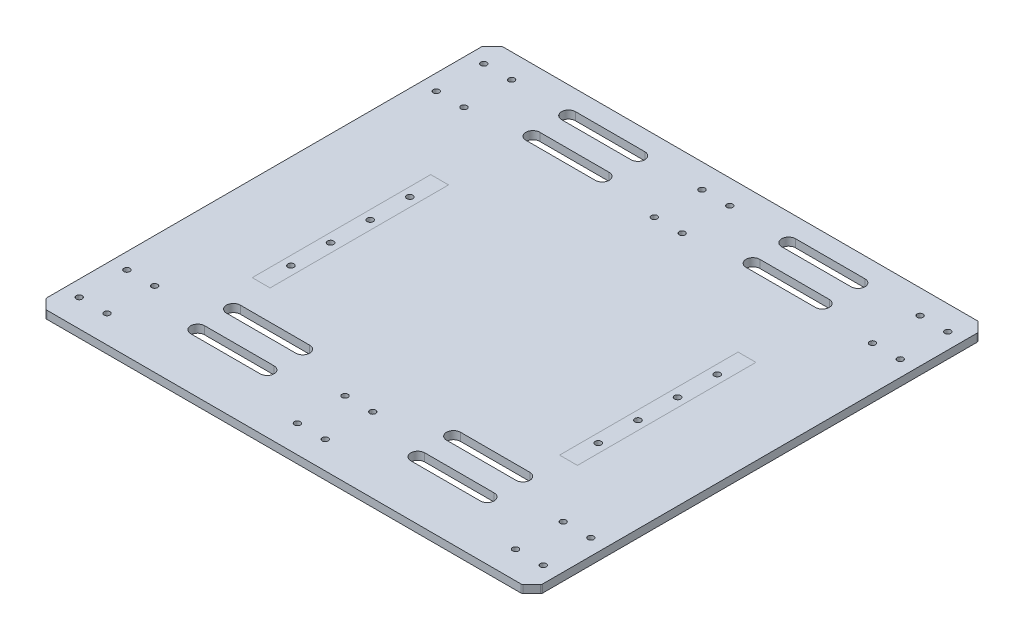
SolidWorks part; units mm, degrees
material "Thornel Mat VMA"
ref_plane "前视基准面" through (0, 0, 0) normal (0, 0, 1) x (1, 0, 0)
ref_plane "上视基准面" through (0, 0, 0) normal (0, 1, 0) x (1, 0, 0)
ref_plane "右视基准面" through (0, 0, 0) normal (1, 0, 0) x (0, 0, -1)
sketch "草图1" plane through (0, 0, 0) normal (0, 1, 0) x (1, 0, 0)
  line L1 (-125, 115) -> (125, 115)
  line L2 (-125, 115) -> (-125, -115)
  line L3 (-125, -115) -> (125, -115)
  line L4 (125, 115) -> (125, -115)
  line L5 (0, -115) -> (0, 115) construction
  line L6 (-125, 0) -> (125, 0) construction
  point P44 (0, 0)
  dimension "D1" = 250
  dimension "D2" = 230
extrude "凸台-拉伸1" add sketch "草图1" along normal blind 4
sketch "草图2" plane through (0, 4, 0) normal (0, 1, 0) x (1, 0, 0)
  line L0 (0, 172.9489) -> (0, 0) construction
  line L1 (0, 0) -> (-225.9448, 0) construction
  line L2 (125, 115) -> (-125, 115) construction
  line L3 (-125, 115) -> (-125, -115) construction
  line L4 (-11, 0) -> (-11, 120.2888) construction
  line L5 (-115, 85) -> (115, 85) construction
  circle A0 centre (-115, 107.5) radius 2.05
  circle A1 centre (-115, 85) radius 2.05
  circle A2 centre (-115, 62.5) radius 2.05
  circle A3 centre (-115, -62.5) radius 2.05
  circle A4 centre (-115, -85) radius 2.05
  circle A5 centre (-115, -107.5) radius 2.05
  circle A6 centre (115, -107.5) radius 2.05
  circle A7 centre (115, -85) radius 2.05
  circle A8 centre (115, -62.5) radius 2.05
  circle A9 centre (115, 62.5) radius 2.05
  circle A10 centre (115, 85) radius 2.05
  circle A11 centre (115, 107.5) radius 2.05
  circle A12 centre (-115, 27.5) radius 2.05
  circle A13 centre (-115, -27.5) radius 2.05
  circle A14 centre (115, -27.5) radius 2.05
  circle A15 centre (115, 27.5) radius 2.05
  circle A16 centre (-11, 27.5) radius 2.05
  circle A17 centre (11, 27.5) radius 2.05
  circle A18 centre (11, -27.5) radius 2.05
  circle A19 centre (-11, -27.5) radius 2.05
  circle A20 centre (-11, 105) radius 2.05
  circle A21 centre (-11, 65) radius 2.05
  circle A22 centre (11, 65) radius 2.05
  circle A23 centre (11, 105) radius 2.05
  circle A24 centre (11, -105) radius 2.05
  circle A25 centre (11, -65) radius 2.05
  circle A26 centre (-11, -65) radius 2.05
  circle A27 centre (-11, -105) radius 2.05
  dimension "D1" = 7.5
  dimension "D2" = 22.5
  dimension "D3" = 22.5
  dimension "D4" = 4.1
  dimension "D5" = 10
  dimension "D6" = 4.1
  dimension "D7" = 27.5
  dimension "D9" = 55
  dimension "D10" = 40
  dimension "D11" = 4.1
  dimension "D8" = 11
extrude "切除-拉伸1" [suppressed] cut sketch "草图2" against normal blind 3
sketch "草图3" [suppressed] plane through (0, 3, 0) normal (0, 1, 0) x (1, 0, 0)
  line L0 (-145, 77.5) -> (145, 77.5) construction
  line L1 (0, 0) -> (0, 207.4838) construction
  line L2 (0, 0) -> (-163.0606, 0) construction
  circle A0 centre (-120, 92.5) radius 2.05
  circle A1 centre (-145, 100) radius 2.05 construction
  circle A2 centre (-120, 62.5) radius 2.05
  circle A3 centre (120, 62.5) radius 2.05
  circle A4 centre (120, 92.5) radius 2.05
  circle A5 centre (120, -92.5) radius 2.05
  circle A6 centre (120, -62.5) radius 2.05
  circle A7 centre (-120, -62.5) radius 2.05
  circle A8 centre (-120, -92.5) radius 2.05
  circle A9 centre (-30, 92.5) radius 2.05
  circle A10 centre (-30, 62.5) radius 2.05
  circle A11 centre (30, 62.5) radius 2.05
  circle A12 centre (30, 92.5) radius 2.05
  circle A13 centre (30, -92.5) radius 2.05
  circle A14 centre (30, -62.5) radius 2.05
  circle A15 centre (-30, -62.5) radius 2.05
  circle A16 centre (-30, -92.5) radius 2.05
  dimension "D1" = 4.1
  dimension "D2" = 30
  dimension "D3" = 25
  dimension "D4" = 4.1
  dimension "D5" = 90
  dimension "D6" = 30
extrude "切除-拉伸2" [suppressed] cut sketch "草图3" against normal blind 3
sketch "草图4" plane through (0, 4, 0) normal (0, 1, 0) x (1, 0, 0)
  circle B0 centre (50, -77.5) radius 15.25 construction
  circle B1 centre (58.8388, -68.6612) radius 1.5 construction
  circle B2 centre (58.8388, -86.3388) radius 1.5 construction
  circle B3 centre (41.1612, -86.3388) radius 1.5 construction
  circle B4 centre (41.1612, -68.6612) radius 1.5 construction
  circle B5 centre (50, -77.5) radius 6 construction
  circle B6 centre (60, 77.5) radius 15.25 construction
  circle B7 centre (68.8388, 68.6612) radius 1.5 construction
  circle B8 centre (68.8388, 86.3388) radius 1.5 construction
  circle B9 centre (51.1612, 86.3388) radius 1.5 construction
  circle B10 centre (51.1612, 68.6612) radius 1.5 construction
  circle B11 centre (60, 77.5) radius 6 construction
  circle B12 centre (-50, 77.5) radius 15.25 construction
  circle B13 centre (-58.8388, 68.6612) radius 1.5 construction
  circle B14 centre (-58.8388, 86.3388) radius 1.5 construction
  circle B15 centre (-41.1612, 86.3388) radius 1.5 construction
  circle B16 centre (-41.1612, 68.6612) radius 1.5 construction
  circle B17 centre (-50, 77.5) radius 6 construction
  circle B18 centre (-50, -77.5) radius 15.25 construction
  circle B19 centre (-58.8388, -68.6612) radius 1.5 construction
  circle B20 centre (-58.8388, -86.3388) radius 1.5 construction
  circle B21 centre (-41.1612, -86.3388) radius 1.5 construction
  circle B22 centre (-41.1612, -68.6612) radius 1.5 construction
  circle B23 centre (-50, -77.5) radius 6 construction
  circle B24 centre (60, -77.5) radius 15.25 construction
  circle B25 centre (68.8388, -68.6612) radius 1.5 construction
  circle B26 centre (68.8388, -86.3388) radius 1.5 construction
  circle B27 centre (51.1612, -86.3388) radius 1.5 construction
  circle B28 centre (51.1612, -68.6612) radius 1.5 construction
  circle B29 centre (60, -77.5) radius 6 construction
  circle B30 centre (-60, -77.5) radius 15.25 construction
  circle B31 centre (-68.8388, -68.6612) radius 1.5 construction
  circle B32 centre (-68.8388, -86.3388) radius 1.5 construction
  circle B33 centre (-51.1612, -86.3388) radius 1.5 construction
  circle B34 centre (-51.1612, -68.6612) radius 1.5 construction
  circle B35 centre (-60, -77.5) radius 6 construction
  circle B36 centre (-60, 77.5) radius 15.25 construction
  circle B37 centre (-68.8388, 68.6612) radius 1.5 construction
  circle B38 centre (-68.8388, 86.3388) radius 1.5 construction
  circle B39 centre (-51.1612, 86.3388) radius 1.5 construction
  circle B40 centre (-51.1612, 68.6612) radius 1.5 construction
  circle B41 centre (-60, 77.5) radius 6 construction
  circle B42 centre (50, 77.5) radius 15.25 construction
  circle B43 centre (58.8388, 68.6612) radius 1.5 construction
  circle B44 centre (58.8388, 86.3388) radius 1.5 construction
  circle B45 centre (41.1612, 86.3388) radius 1.5 construction
  circle B46 centre (41.1612, 68.6612) radius 1.5 construction
  circle B47 centre (50, 77.5) radius 6 construction
  line B48 (50, -77.5) -> (41.1612, -68.6612) construction
  line B49 (0, -217.5) -> (0, 150.3134) construction
  line B50 (60, -77.5) -> (51.1612, -68.6612) construction
  line B51 (145, 77.5) -> (145, -77.5) construction
  line B52 (145, 0) -> (-145, 0) construction
  line B53 (60, 77.5) -> (51.1612, 68.6612) construction
  line B54 (50, 77.5) -> (41.1612, 68.6612) construction
  line B55 (-55, 77.5) -> (3.1224, 77.5) construction
  line B56 (50, -77.5) -> (60, -77.5) construction
  line B57 (50, -61.5) -> (60, -61.5) construction
  line B58 (50, -93.5) -> (60, -93.5) construction
  line B59 (-50, -77.5) -> (-60, -77.5) construction
  line B60 (-50, -61.5) -> (-60, -61.5) construction
  line B61 (-50, -93.5) -> (-60, -93.5) construction
  line B62 (-50, 77.5) -> (-60, 77.5) construction
  line B63 (-50, 61.5) -> (-60, 61.5) construction
  line B64 (-50, 93.5) -> (-60, 93.5) construction
  line B65 (50, 77.5) -> (60, 77.5) construction
  line B66 (50, 61.5) -> (60, 61.5) construction
  line B67 (50, 93.5) -> (60, 93.5) construction
  line B68 (-68.8388, 86.3388) -> (-41.1612, 86.3388) construction
  line B69 (-68.8388, 89.8388) -> (-41.1612, 89.8388)
  line B70 (-68.8388, 82.8388) -> (-41.1612, 82.8388)
  line B71 (68.8388, 86.3388) -> (41.1612, 86.3388) construction
  line B72 (68.8388, 89.8388) -> (41.1612, 89.8388)
  line B73 (68.8388, 82.8388) -> (41.1612, 82.8388)
  line B74 (68.8388, 68.6612) -> (41.1612, 68.6612) construction
  line B75 (68.8388, 65.1612) -> (41.1612, 65.1612)
  line B76 (68.8388, 72.1612) -> (41.1612, 72.1612)
  line B77 (-68.8388, 68.6612) -> (-41.1612, 68.6612) construction
  line B78 (-68.8388, 65.1612) -> (-41.1612, 65.1612)
  line B79 (-68.8388, 72.1612) -> (-41.1612, 72.1612)
  line B80 (-68.8388, -86.3388) -> (-41.1612, -86.3388) construction
  line B81 (-68.8388, -89.8388) -> (-41.1612, -89.8388)
  line B82 (-68.8388, -82.8388) -> (-41.1612, -82.8388)
  line B83 (-68.8388, -68.6612) -> (-41.1612, -68.6612) construction
  line B84 (-68.8388, -65.1612) -> (-41.1612, -65.1612)
  line B85 (-68.8388, -72.1612) -> (-41.1612, -72.1612)
  line B86 (68.8388, -86.3388) -> (41.1612, -86.3388) construction
  line B87 (68.8388, -89.8388) -> (41.1612, -89.8388)
  line B88 (68.8388, -82.8388) -> (41.1612, -82.8388)
  line B89 (68.8388, -68.6612) -> (41.1612, -68.6612) construction
  line B90 (68.8388, -65.1612) -> (41.1612, -65.1612)
  line B91 (68.8388, -72.1612) -> (41.1612, -72.1612)
  arc B92 (50, -61.5) -> (50, -93.5) centre (50, -77.5) ccw construction
  arc B93 (60, -93.5) -> (60, -61.5) centre (60, -77.5) ccw construction
  arc B94 (-50, -61.5) -> (-50, -93.5) centre (-50, -77.5) cw construction
  arc B95 (-60, -93.5) -> (-60, -61.5) centre (-60, -77.5) cw construction
  arc B96 (-50, 61.5) -> (-50, 93.5) centre (-50, 77.5) ccw construction
  arc B97 (-60, 93.5) -> (-60, 61.5) centre (-60, 77.5) ccw construction
  arc B98 (50, 61.5) -> (50, 93.5) centre (50, 77.5) cw construction
  arc B99 (60, 93.5) -> (60, 61.5) centre (60, 77.5) cw construction
  arc B100 (-68.8388, 89.8388) -> (-68.8388, 82.8388) centre (-68.8388, 86.3388) ccw
  arc B101 (-41.1612, 82.8388) -> (-41.1612, 89.8388) centre (-41.1612, 86.3388) ccw
  arc B102 (68.8388, 89.8388) -> (68.8388, 82.8388) centre (68.8388, 86.3388) cw
  arc B103 (41.1612, 82.8388) -> (41.1612, 89.8388) centre (41.1612, 86.3388) cw
  arc B104 (68.8388, 65.1612) -> (68.8388, 72.1612) centre (68.8388, 68.6612) ccw
  arc B105 (41.1612, 72.1612) -> (41.1612, 65.1612) centre (41.1612, 68.6612) ccw
  arc B106 (-68.8388, 65.1612) -> (-68.8388, 72.1612) centre (-68.8388, 68.6612) cw
  arc B107 (-41.1612, 72.1612) -> (-41.1612, 65.1612) centre (-41.1612, 68.6612) cw
  arc B108 (-68.8388, -89.8388) -> (-68.8388, -82.8388) centre (-68.8388, -86.3388) cw
  arc B109 (-41.1612, -82.8388) -> (-41.1612, -89.8388) centre (-41.1612, -86.3388) cw
  arc B110 (-68.8388, -65.1612) -> (-68.8388, -72.1612) centre (-68.8388, -68.6612) ccw
  arc B111 (-41.1612, -72.1612) -> (-41.1612, -65.1612) centre (-41.1612, -68.6612) ccw
  arc B112 (68.8388, -89.8388) -> (68.8388, -82.8388) centre (68.8388, -86.3388) ccw
  arc B113 (41.1612, -82.8388) -> (41.1612, -89.8388) centre (41.1612, -86.3388) ccw
  arc B114 (68.8388, -65.1612) -> (68.8388, -72.1612) centre (68.8388, -68.6612) cw
  arc B115 (41.1612, -72.1612) -> (41.1612, -65.1612) centre (41.1612, -68.6612) cw
sketch_block_instance "槽口-1"
sketch_block "槽口" parameters "D3"=16, "D4"=3.5, "D5"=3.5, "D1"=100, "D2"=120
sketch_block_instance "3510电机安装孔位-1"
sketch_block "3510电机安装孔位"
sketch_block_instance "3510电机安装孔位-1"
sketch_block_instance "3510电机安装孔位-2"
sketch_block_instance "3510电机安装孔位-3"
sketch_block_instance "3510电机安装孔位-4"
sketch_block_instance "3510电机安装孔位-5"
sketch_block_instance "3510电机安装孔位-6"
sketch_block_instance "3510电机安装孔位-7"
extrude "切除-拉伸3" [suppressed] cut sketch "草图4" against normal blind 3 contours B70 B101 B69 B100 | B107 B79 B106 B78 | B103 B73 B102 B72 | B76 B105 B75 B104 | B115 B91 B114 B90 | B88 B113 B87 B112 | B85 B111 B84 B110 | B109 B82 B108 B81
sketch "草图5" plane through (0, 4, 0) normal (0, 1, 0) x (1, 0, 0)
  line L0 (0, 125.0534) -> (0, -12) construction
  line L1 (0, -12) -> (98.1075, -12) construction
  line L2 (77.5, 34.0359) -> (77.5, -32.2485) construction
  circle A0 centre (77.5, -2) radius 1.55
  circle A1 centre (77.5, 18) radius 1.55
  circle A2 centre (77.5, -22) radius 1.55
  circle A3 centre (77.5, -42) radius 1.55
  circle A4 centre (-77.5, -42) radius 1.55
  circle A5 centre (-77.5, -22) radius 1.55
  circle A6 centre (-77.5, 18) radius 1.55
  circle A7 centre (-77.5, -2) radius 1.55
  dimension "D2" = 3.1
  dimension "D3" = 20
  dimension "D4" = 20
  dimension "D1" = 77.5
  dimension "D5" = 12
extrude "切除-拉伸4" cut sketch "草图5" against normal blind 3
sketch "草图6" plane through (0, 4, 0) normal (0, 1, 0) x (1, 0, 0)
  line L0 (-77.5, 18) -> (-77.5, -42) construction
  line L1 (-73, 33) -> (-82, 33)
  line L2 (-73, 33) -> (-73, -57)
  line L3 (-73, -57) -> (-82, -57)
  line L4 (-82, 33) -> (-82, -57)
  line L5 (-77.5, -57) -> (-77.5, 33) construction
  line L6 (-73, -12) -> (-82, -12) construction
  line L7 (0, 0) -> (0, 69.9074) construction
  line L8 (73, -57) -> (82, -57)
  line L9 (82, 33) -> (82, -57)
  line L10 (73, 33) -> (82, 33)
  line L11 (73, 33) -> (73, -57)
  point P84 (-77.5, -12)
  dimension "D1" = 90
  dimension "D2" = 9
split line "分割线1"
sketch "草图7" plane through (0, 4, 0) normal (0, 1, 0) x (1, 0, 0)
  circle A0 centre (-117, 94.787) radius 1.5 construction
  circle A1 centre (-117, 70.787) radius 1.5 construction
  circle A2 centre (-103, 70.787) radius 1.5 construction
  circle A3 centre (-103, 94.787) radius 1.5 construction
  circle A4 centre (-7, 94.787) radius 1.5 construction
  circle A5 centre (7, 94.787) radius 1.5 construction
  circle A6 centre (7, 70.787) radius 1.5 construction
  circle A7 centre (-7, 70.787) radius 1.5 construction
  circle A8 centre (117, 94.787) radius 1.5 construction
  circle A9 centre (117, 70.787) radius 1.5 construction
  circle A10 centre (103, 70.787) radius 1.5 construction
  circle A11 centre (103, 94.787) radius 1.5 construction
  circle A12 centre (103, -109.213) radius 1.5 construction
  circle A13 centre (117, -109.213) radius 1.5 construction
  circle A14 centre (117, -85.213) radius 1.5 construction
  circle A15 centre (103, -85.213) radius 1.5 construction
  circle A16 centre (7, -85.213) radius 1.5 construction
  circle A17 centre (7, -109.213) radius 1.5 construction
  circle A18 centre (-7, -85.213) radius 1.5 construction
  circle A19 centre (-7, -109.213) radius 1.5 construction
  circle A20 centre (-117, -85.213) radius 1.5 construction
  circle A21 centre (-103, -85.213) radius 1.5 construction
  circle A22 centre (-103, -109.213) radius 1.5 construction
  circle A23 centre (-117, -109.213) radius 1.5 construction
  circle A24 centre (-117, 94.787) radius 1.5
  circle A25 centre (-117, 70.787) radius 1.5
  circle A26 centre (-103, 70.787) radius 1.5
  circle A27 centre (-103, 94.787) radius 1.5
  circle A28 centre (-7, 94.787) radius 1.5
  circle A29 centre (7, 94.787) radius 1.5
  circle A30 centre (7, 70.787) radius 1.5
  circle A31 centre (-7, 70.787) radius 1.5
  circle A32 centre (117, 94.787) radius 1.5
  circle A33 centre (117, 70.787) radius 1.5
  circle A34 centre (103, 70.787) radius 1.5
  circle A35 centre (103, 94.787) radius 1.5
  circle A36 centre (103, -109.213) radius 1.5
  circle A37 centre (117, -109.213) radius 1.5
  circle A38 centre (117, -85.213) radius 1.5
  circle A39 centre (103, -85.213) radius 1.5
  circle A40 centre (7, -85.213) radius 1.5
  circle A41 centre (7, -109.213) radius 1.5
  circle A42 centre (-7, -85.213) radius 1.5
  circle A43 centre (-7, -109.213) radius 1.5
  circle A44 centre (-117, -85.213) radius 1.5
  circle A45 centre (-103, -85.213) radius 1.5
  circle A46 centre (-103, -109.213) radius 1.5
  circle A47 centre (-117, -109.213) radius 1.5
extrude "切除-拉伸5" cut sketch "草图7" against normal through all
sketch "草图8" plane through (0, 4, 0) normal (0, 1, 0) x (1, 0, 0)
  line L0 (-73, 93.5) -> (-38, 93.5) construction
  line L1 (-73, 97) -> (-38, 97)
  line L2 (-73, 90) -> (-38, 90)
  line L3 (0, 129.0906) -> (0, -58.3357) construction
  line L4 (-104.3355, 0) -> (119.4962, 0) construction
  line L5 (125, 115) -> (-125, 115) construction
  line L6 (-73, 75.5) -> (-38, 75.5) construction
  line L7 (-73, 79) -> (-38, 79)
  line L8 (-73, 72) -> (-38, 72)
  line L9 (-73, 57.5) -> (-38, 57.5) construction
  line L10 (-73, 61) -> (-38, 61) construction
  line L11 (-73, 54) -> (-38, 54) construction
  line L12 (73, 93.5) -> (38, 93.5) construction
  line L13 (73, 97) -> (38, 97)
  line L14 (73, 90) -> (38, 90)
  line L15 (73, 75.5) -> (38, 75.5) construction
  line L16 (73, 79) -> (38, 79)
  line L17 (73, 72) -> (38, 72)
  line L18 (73, 57.5) -> (38, 57.5) construction
  line L19 (73, 61) -> (38, 61) construction
  line L20 (73, 54) -> (38, 54) construction
  line L21 (-73, -93.5) -> (-38, -93.5) construction
  line L22 (-73, -97) -> (-38, -97)
  line L23 (-73, -90) -> (-38, -90)
  line L24 (-73, -75.5) -> (-38, -75.5) construction
  line L25 (-73, -79) -> (-38, -79)
  line L26 (-73, -72) -> (-38, -72)
  line L27 (-73, -57.5) -> (-38, -57.5) construction
  line L28 (-73, -61) -> (-38, -61) construction
  line L29 (-73, -54) -> (-38, -54) construction
  line L30 (73, -93.5) -> (38, -93.5) construction
  line L31 (73, -97) -> (38, -97)
  line L32 (73, -90) -> (38, -90)
  line L33 (73, -75.5) -> (38, -75.5) construction
  line L34 (73, -79) -> (38, -79)
  line L35 (73, -72) -> (38, -72)
  line L36 (73, -57.5) -> (38, -57.5) construction
  line L37 (73, -61) -> (38, -61) construction
  line L38 (73, -54) -> (38, -54) construction
  line L39 (125, -115) -> (125, 115) construction
  line L40 (-125, 115) -> (125, 115)
  line L41 (-125, 115) -> (-125, 107)
  line L42 (-125, 107) -> (125, 107)
  line L43 (125, 115) -> (125, 107)
  arc A0 (-73, 97) -> (-73, 90) centre (-73, 93.5) ccw
  arc A1 (-38, 90) -> (-38, 97) centre (-38, 93.5) ccw
  arc A2 (-73, 79) -> (-73, 72) centre (-73, 75.5) ccw
  arc A3 (-38, 72) -> (-38, 79) centre (-38, 75.5) ccw
  arc A4 (-73, 61) -> (-73, 54) centre (-73, 57.5) ccw construction
  arc A5 (-38, 54) -> (-38, 61) centre (-38, 57.5) ccw construction
  arc A6 (73, 97) -> (73, 90) centre (73, 93.5) cw
  arc A7 (38, 90) -> (38, 97) centre (38, 93.5) cw
  arc A8 (73, 79) -> (73, 72) centre (73, 75.5) cw
  arc A9 (38, 72) -> (38, 79) centre (38, 75.5) cw
  arc A10 (73, 61) -> (73, 54) centre (73, 57.5) cw construction
  arc A11 (38, 54) -> (38, 61) centre (38, 57.5) cw construction
  arc A12 (-73, -97) -> (-73, -90) centre (-73, -93.5) cw
  arc A13 (-38, -90) -> (-38, -97) centre (-38, -93.5) cw
  arc A14 (-73, -79) -> (-73, -72) centre (-73, -75.5) cw
  arc A15 (-38, -72) -> (-38, -79) centre (-38, -75.5) cw
  arc A16 (-73, -61) -> (-73, -54) centre (-73, -57.5) cw construction
  arc A17 (-38, -54) -> (-38, -61) centre (-38, -57.5) cw construction
  arc A18 (73, -97) -> (73, -90) centre (73, -93.5) ccw
  arc A19 (38, -90) -> (38, -97) centre (38, -93.5) ccw
  arc A20 (73, -79) -> (73, -72) centre (73, -75.5) ccw
  arc A21 (38, -72) -> (38, -79) centre (38, -75.5) ccw
  arc A22 (73, -61) -> (73, -54) centre (73, -57.5) ccw construction
  arc A23 (38, -54) -> (38, -61) centre (38, -57.5) ccw construction
  point P2 (-55.5, 93.5)
  point P17 (-55.5, 75.5)
  point P24 (-55.5, 57.5)
  point P30 (55.5, 93.5)
  point P37 (55.5, 75.5)
  point P44 (55.5, 57.5)
  point P51 (-55.5, -93.5)
  point P58 (-55.5, -75.5)
  point P65 (-55.5, -57.5)
  point P72 (55.5, -93.5)
  point P79 (55.5, -75.5)
  point P86 (55.5, -57.5)
  dimension "D1" = 3.5
  dimension "D2" = 35
  dimension "D3" = 18
  dimension "D4" = 38
  dimension "D6" = 18
  dimension "D7" = 8
  dimension "D5" = 3
extrude "切除-拉伸6" cut sketch "草图8" against normal blind 10
sketch "草图9" plane through (0, 4, 0) normal (0, 1, 0) x (1, 0, 0)
  line L0 (125, -115) -> (125, 107) construction
  line L1 (-125, -115) -> (125, -115)
  line L2 (-125, -115) -> (-125, -123)
  line L3 (-125, -123) -> (125, -123)
  line L4 (125, -115) -> (125, -123)
  dimension "D1" = 8
extrude "凸台-拉伸2" add sketch "草图9" against normal up to surface (4 mm away) up to face at (-55.5, 0, 93.5)
chamfer "倒角1" distance 5 angle 45 4 edges at (-125, 2, 123) (125, 2, -107) (-125, 2, -107) (125, 2, 123)
fillet "圆角1" radius 1 8 edges at (-125, 2, -102) (-120, 2, -107) (120, 2, -107) (125, 2, -102) (-120, 2, 123) (-125, 2, 118) (125, 2, 118) (120, 2, 123)
